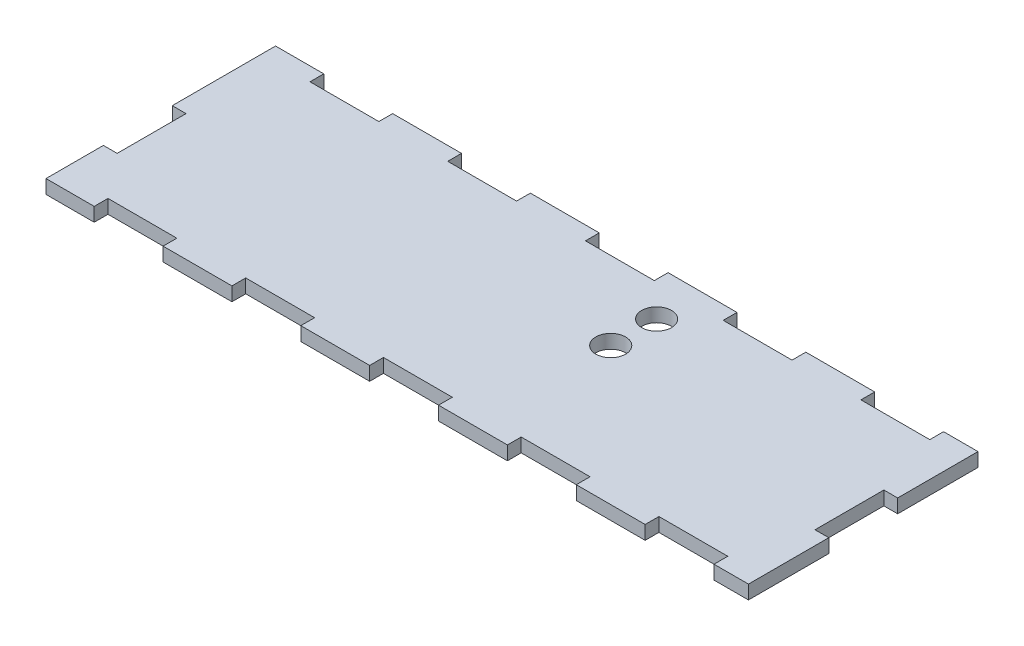
SolidWorks part; units mm, degrees
ref_plane "Alzado" through (0, 0, 0) normal (0, 0, 1) x (1, 0, 0)
ref_plane "Planta" through (0, 0, 0) normal (0, 1, 0) x (1, 0, 0)
ref_plane "Vista lateral" through (0, 0, 0) normal (1, 0, 0) x (0, 0, -1)
sketch "Croquis1" plane through (0, 0, 0) normal (0, 1, 0) x (1, 0, 0)
  line L0 (0, 0) -> (10.5, 0)
  line L1 (0, 40) -> (0, 50)
  line L2 (3, 50) -> (10.5, 50)
  line L3 (153, 50) -> (153, 32.5)
  line L4 (0, 0) -> (0, 12.5)
  line L6 (3, 20) -> (3, 27.5)
  line L7 (3, 27.5) -> (0, 27.5)
  line L8 (3, 20) -> (3, 12.5)
  line L9 (3, 12.5) -> (0, 12.5)
  line L11 (3, 50) -> (10.5, 50)
  line L12 (93, 50) -> (93, 30) construction
  line L13 (0, 27.5) -> (0, 40)
  line L14 (70.5, 50) -> (67.6088, 50)
  line L15 (85.5, 47) -> (70.5, 47)
  line L16 (70.5, 47) -> (70.5, 50)
  line L17 (70.5, 50) -> (55.5, 50)
  line L18 (55.5, 50) -> (55.5, 47)
  line L19 (55.5, 47) -> (40.5, 47)
  line L20 (40.5, 47) -> (40.5, 50)
  line L21 (40.5, 50) -> (25.5, 50)
  line L22 (25.5, 50) -> (25.5, 47)
  line L23 (25.5, 47) -> (10.5, 47)
  line L24 (10.5, 47) -> (10.5, 50)
  line L25 (145.5, 47) -> (145.5, 50)
  line L26 (130.5, 47) -> (145.5, 47)
  line L27 (130.5, 50) -> (130.5, 47)
  line L28 (115.5, 47) -> (115.5, 50)
  line L29 (100.5, 47) -> (115.5, 47)
  line L30 (100.5, 50) -> (100.5, 47)
  line L31 (85.5, 47) -> (85.5, 50)
  line L32 (0, 50) -> (3, 50)
  line L33 (150, 25) -> (150, 32.5)
  line L34 (150, 32.5) -> (153, 32.5)
  line L35 (150, 25) -> (150, 17.5)
  line L36 (150, 17.5) -> (153, 17.5)
  line L37 (25.5, 0) -> (40.5, 0)
  line L38 (85.5, 3) -> (85.5, 0)
  line L39 (100.5, 0) -> (100.5, 3)
  line L40 (100.5, 3) -> (115.5, 3)
  line L41 (115.5, 3) -> (115.5, 0)
  line L42 (130.5, 0) -> (130.5, 3)
  line L43 (130.5, 3) -> (145.5, 3)
  line L44 (145.5, 3) -> (145.5, 0)
  line L45 (10.5, 3) -> (10.5, 0)
  line L46 (25.5, 3) -> (10.5, 3)
  line L47 (25.5, 0) -> (25.5, 3)
  line L48 (40.5, 3) -> (40.5, 0)
  line L49 (55.5, 3) -> (40.5, 3)
  line L50 (55.5, 0) -> (55.5, 3)
  line L51 (70.5, 3) -> (70.5, 0)
  line L52 (85.5, 3) -> (70.5, 3)
  line L53 (55.5, 0) -> (70.5, 0)
  line L54 (85.5, 0) -> (100.5, 0)
  line L55 (115.5, 0) -> (130.5, 0)
  line L56 (145.5, 0) -> (153, 0)
  line L57 (153, 17.5) -> (153, 0)
  line L58 (145.5, 50) -> (153, 50)
  line L59 (115.5, 50) -> (130.5, 50)
  line L60 (85.5, 50) -> (100.5, 50)
  line L61 (85.5, 50) -> (93, 50)
  line L62 (55.5, 50) -> (70.5, 50)
  line L63 (55.5, 50) -> (70.5, 50)
  line L64 (25.5, 50) -> (40.5, 50)
  line L65 (25.5, 50) -> (40.5, 50)
  circle A0 centre (93, 30) radius 3.25
  circle A1 centre (93, 40) radius 3.25
  dimension "D9" = 6.5
  dimension "D2" = 6.5
  dimension "D1" = 153
  dimension "D3" = 40
  dimension "D5" = 7.5
  dimension "D6" = 7.5
  dimension "D7" = 90
  dimension "D8" = 20
  dimension "D11" = 15
  dimension "D12" = 15
  dimension "D13" = 15
  dimension "D14" = 15
  dimension "D16" = 7.5
  dimension "D17" = 7.5
extrude "Saliente-Extruir1" add sketch "Croquis1" along normal blind 3
